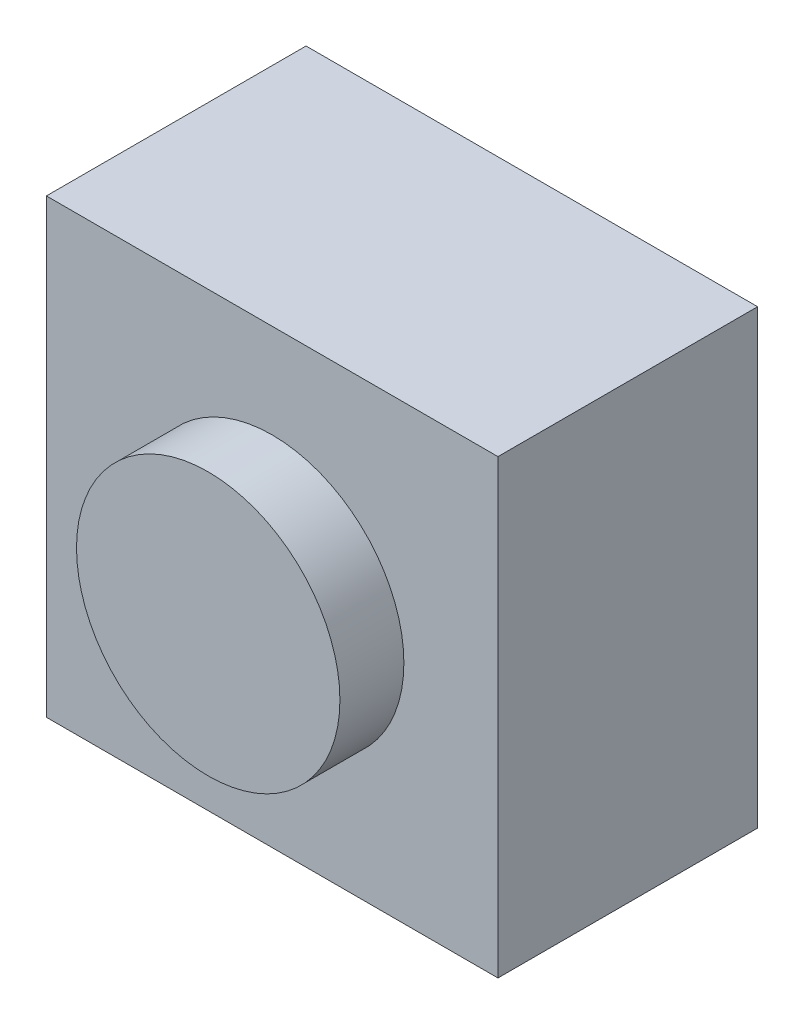
SolidWorks part; units mm, degrees
ref_plane "Front Plane" through (0, 0, 0) normal (0, 0, 1) x (1, 0, 0)
ref_plane "Top Plane" through (0, 0, 0) normal (0, 1, 0) x (1, 0, 0)
ref_plane "Right Plane" through (0, 0, 0) normal (1, 0, 0) x (0, 0, -1)
sketch "Sketch1" plane through (0, 0, 0) normal (0, 0, 1) x (1, 0, 0)
  line L1 (3, 3) -> (-3, 3)
  line L2 (3, 3) -> (3, -3)
  line L3 (3, -3) -> (-3, -3)
  line L4 (-3, 3) -> (-3, -3)
  line L5 (3, 3) -> (-3, -3) construction
  line L6 (3, -3) -> (-3, 3) construction
  point P0 (0, 0)
  dimension "D1" = 6
extrude "Boss-Extrude1" add sketch "Sketch1" along normal blind 3.45
sketch "Sketch2" plane through (0, 0, 3.45) normal (0, 0, 1) x (1, 0, 0)
  circle A0 centre (0, 0) radius 1.75
  dimension "D1" = 3.5
extrude "Boss-Extrude3" add sketch "Sketch2" along normal offset from surface (0.85 mm away) 4.3 up to face at (0, 0, 0)
